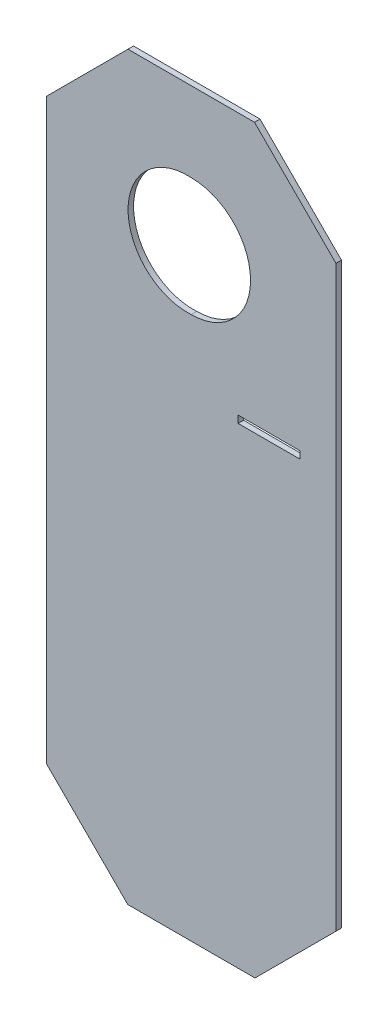
SolidWorks part; units mm, degrees
ref_plane "Спереди" through (0, 0, 0) normal (0, 0, 1) x (1, 0, 0)
ref_plane "Сверху" through (0, 0, 0) normal (0, 1, 0) x (1, 0, 0)
ref_plane "Справа" through (0, 0, 0) normal (1, 0, 0) x (0, 0, -1)
sketch "Эскиз1" plane through (0, 0, 0) normal (0, 0, 1) x (1, 0, 0)
  line L0 (105.0829, 581.7221) -> (45.979, 640.8259)
  line L1 (45.979, 640.8259) -> (-45.8132, 640.8259)
  line L2 (-45.8132, 640.8259) -> (-104.9171, 581.7221)
  line L3 (-104.9171, 581.7221) -> (-104.9171, 162.2129)
  line L4 (-104.9171, 162.2129) -> (-45.9732, 103.269)
  line L5 (-45.9732, 103.269) -> (46.3268, 103.269)
  line L6 (46.3268, 103.269) -> (105.0829, 162.0251)
  line L7 (105.0829, 162.0251) -> (105.0829, 581.7221)
  line L8 (0.0829, 640.8259) -> (0.0829, 703.4762) construction
  dimension "D1" = 105
  dimension "D2" = 105
extrude "Вытянуть1" add sketch "Эскиз1" along normal blind 4
sketch "Эскиз2" plane through (0, 0, 4) normal (0, 0, 1) x (1, 0, 0)
  line L0 (0.1173, 583.0246) -> (0.1173, 601.8308) construction
  arc A0 (0.1173, 497.0246) -> (0.1173, 583.0246) centre (0.1173, 540.0246) ccw
  arc A2 (0.1173, 583.0246) -> (0.1173, 497.0246) centre (-2.6747, 540.0246) ccw
extrude "Вырез-Вытянуть1" cut sketch "Эскиз2" against normal through all
sketch "Эскиз3" plane through (0, 0, 0) normal (0, 0, -1) x (-1, 0, 0)
  line L1 (-34.1142, 450.8759) -> (-79.1142, 450.8759)
  line L2 (-34.1142, 450.8759) -> (-34.1142, 445.6259)
  line L3 (-34.1142, 445.6259) -> (-79.1142, 445.6259)
  line L4 (-79.1142, 450.8759) -> (-79.1142, 445.6259)
extrude "Вырез-Вытянуть2" cut sketch "Эскиз3" against normal through all
